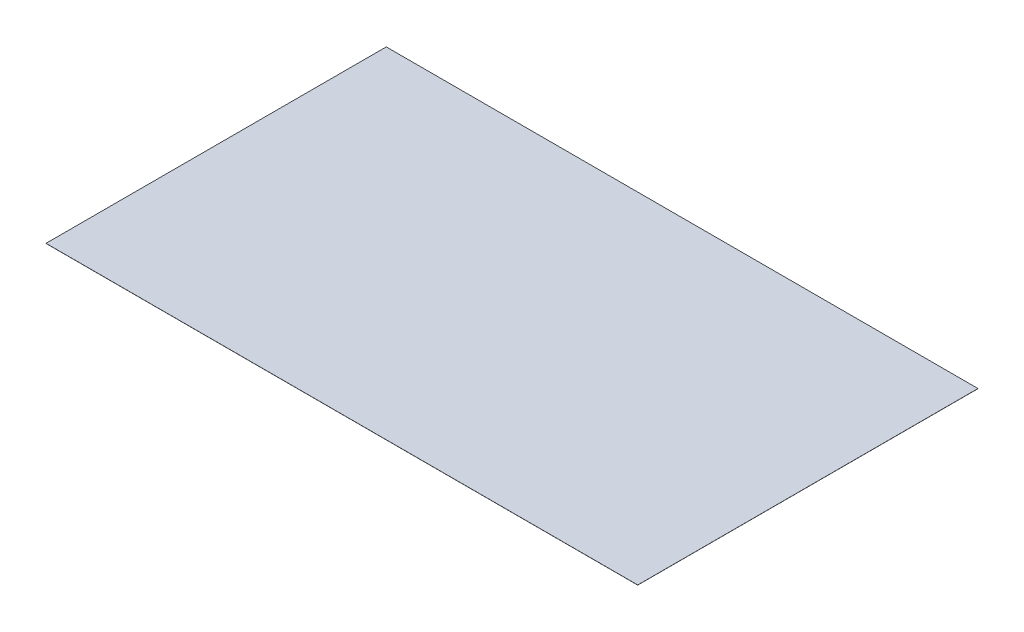
SolidWorks part; units mm, degrees
ref_plane "Front Plane" through (0, 0, 0) normal (0, 0, 1) x (1, 0, 0)
ref_plane "Top Plane" through (0, 0, 0) normal (0, 1, 0) x (1, 0, 0)
ref_plane "Right Plane" through (0, 0, 0) normal (1, 0, 0) x (0, 0, -1)
sketch "Sketch1" plane through (0, 0, 0) normal (0, 1, 0) x (1, 0, 0)
  line L1 (6096, -3505.2) -> (-6096, -3505.2)
  line L2 (6096, -3505.2) -> (6096, 3505.2)
  line L3 (6096, 3505.2) -> (-6096, 3505.2)
  line L4 (-6096, -3505.2) -> (-6096, 3505.2)
  line L5 (6096, -3505.2) -> (-6096, 3505.2) construction
  line L6 (6096, 3505.2) -> (-6096, -3505.2) construction
  point P0 (0, 0)
  dimension "D1" = 12192
  dimension "D2" = 7010.4
extrude "Base" add sketch "Sketch1" along normal blind 2.54
